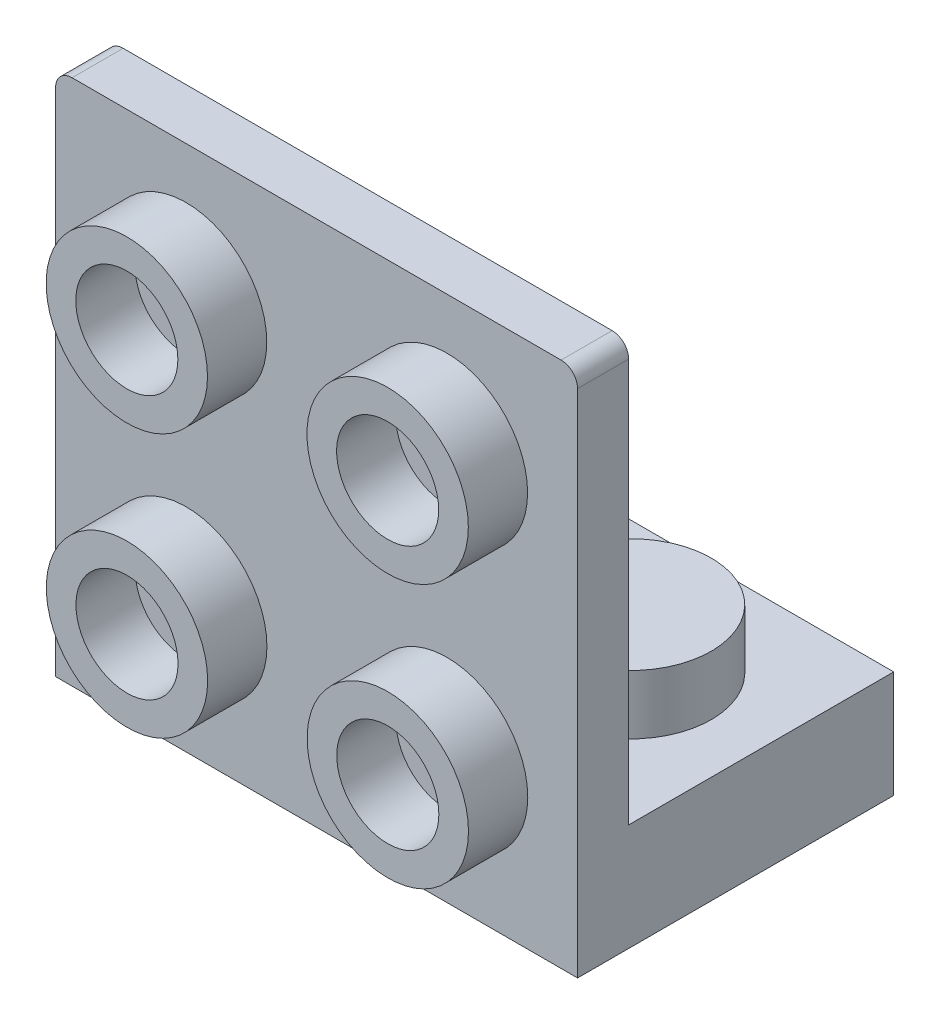
SolidWorks part; units mm, degrees
ref_plane "Front Plane" through (0, 0, 0) normal (0, 0, 1) x (1, 0, 0)
ref_plane "Top Plane" through (0, 0, 0) normal (0, 1, 0) x (1, 0, 0)
ref_plane "Right Plane" through (0, 0, 0) normal (1, 0, 0) x (0, 0, -1)
sketch "Sketch1" plane through (0, 0, 0) normal (1, 0, 0) x (0, 0, -1)
  line L0 (0, 16) -> (0, 0)
  line L1 (0, 0) -> (9.6, 0)
  line L2 (9.6, 0) -> (9.6, 3.25)
  line L3 (9.6, 3.25) -> (1.55, 3.25)
  line L4 (1.55, 3.25) -> (1.55, 16)
  line L5 (1.55, 16) -> (0, 16)
  dimension "D1" = 1.55
  dimension "D2" = 16
  dimension "D3" = 9.6
  dimension "D4" = 12.75
extrude "Boss-Extrude1" add sketch "Sketch1" against normal blind 15.85
sketch "Sketch2" plane through (0, 3.25, 0) normal (0, 1, 0) x (1, 0, 0)
  line L1 (-15.85, 9.6) -> (-15.85, 1.55) construction
  line L2 (0, 9.6) -> (0, 1.55) construction
  line L3 (-15.85, 9.6) -> (0, 9.6) construction
  circle A0 centre (-11.8875, 5.575) radius 2.45
  circle A1 centre (-3.9625, 5.575) radius 2.45
  dimension "D1" = 3.9625
  dimension "D2" = 3.9625
  dimension "D5" = 4.9
  dimension "D6" = 4.9
  dimension "D3" = 4.025
  dimension "D4" = 4.025
extrude "Boss-Extrude2" add sketch "Sketch2" along normal blind 1.8
sketch "Sketch3" plane through (0, 0, 0) normal (0, -1, 0) x (1, 0, 0)
  line L0 (-15.85, -9.6) -> (0, -9.6) construction
  line L1 (-14.35, -1.6) -> (-1.5, -1.6)
  line L2 (-14.35, -1.6) -> (-14.35, -8.1)
  line L3 (-14.35, -8.1) -> (-1.5, -8.1)
  line L4 (-1.5, -1.6) -> (-1.5, -8.1)
  line L5 (-14.35, -1.6) -> (-1.5, -8.1) construction
  line L6 (-14.35, -8.1) -> (-1.5, -1.6) construction
  line L7 (0, 0) -> (0, -9.6) construction
  line L8 (-15.85, 0) -> (-15.85, -9.6) construction
  line L9 (-15.85, 0) -> (0, 0) construction
  point P0 (-7.925, -4.85)
  dimension "D1" = 1.5
  dimension "D2" = 1.5
  dimension "D3" = 1.5
  dimension "D4" = 1.6
extrude "Cut-Extrude1" cut sketch "Sketch3" against normal blind 2.05
sketch "Sketch4" plane through (0, 2.05, 0) normal (0, -1, 0) x (1, 0, 0)
  line L0 (-15.85, -9.6) -> (0, -9.6) construction
  circle A0 centre (-11.8875, -5.575) radius 0.95
  circle A1 centre (-3.9625, -5.575) radius 0.95
  dimension "D1" = 1.9
  dimension "D2" = 1.9
extrude "Cut-Extrude2" cut sketch "Sketch4" against normal offset from surface (1.5 mm away) 1.5 up to face at (-11.8875, 5.05, -3.125)
sketch "Sketch5" plane through (0, 2.05, 0) normal (0, -1, 0) x (1, 0, 0)
  line L0 (-15.85, 0) -> (-15.85, -9.6) construction
  line L2 (-15.85, -9.6) -> (0, -9.6) construction
  circle A0 centre (-7.925, -5.57) radius 1.5
  circle A1 centre (-7.925, -5.57) radius 0.7
  dimension "D1" = 3
  dimension "D2" = 1.4
  dimension "D4" = 4.03
  dimension "D3" = 7.925
extrude "Boss-Extrude3" add sketch "Sketch5" along normal offset from surface (1.85 mm away) 0.2 up to face at (-7.925, 0, -4.85)
sketch "Sketch6" plane through (0, 0, 0) normal (0, 0, 1) x (1, 0, 0)
  line L1 (-15.85, 16) -> (0, 16) construction
  line L2 (-15.85, 16) -> (-15.85, 0) construction
  line L3 (0, 16) -> (0, 0) construction
  circle A0 centre (-11.8875, 12) radius 2.45
  circle A1 centre (-11.8875, 12) radius 1.55
  circle A2 centre (-3.9675, 12) radius 1.55
  circle A3 centre (-3.9675, 12) radius 2.45
  circle A4 centre (-3.9625, 4) radius 1.55
  circle A5 centre (-3.9625, 4) radius 2.45
  circle A6 centre (-11.8825, 4) radius 1.55
  circle A7 centre (-11.8825, 4) radius 2.45
  dimension "D3" = 4.9
  dimension "D4" = 3.1
  dimension "D7" = 7.92
  dimension "D8" = 8
  dimension "D9" = 3.9625
  dimension "D1" = 4
  dimension "D2" = 3.9625
  dimension "D5" = 2
  dimension "D6" = 2
extrude "Boss-Extrude4" add sketch "Sketch6" along normal blind 1.8
fillet "Fillet1" radius 0.5 2 edges at (0, 16, -0.775) (-15.85, 16, -0.775)
